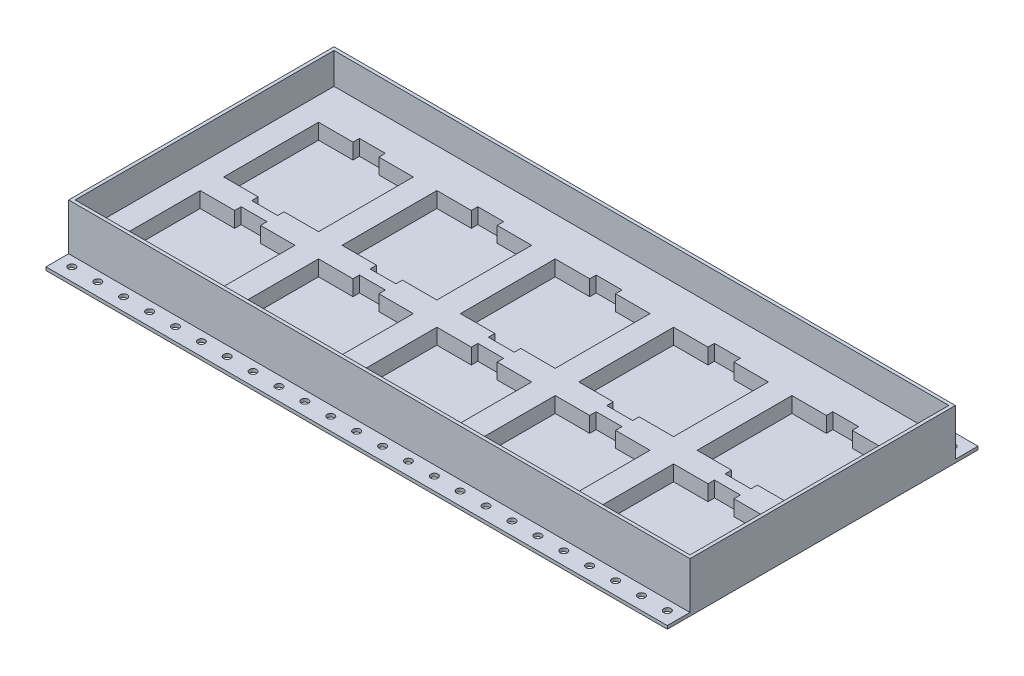
SolidWorks part; units mm, degrees
ref_plane "Front Plane" through (0, 0, 0) normal (0, 0, 1) x (1, 0, 0)
ref_plane "Top Plane" through (0, 0, 0) normal (0, 1, 0) x (1, 0, 0)
ref_plane "Right Plane" through (0, 0, 0) normal (1, 0, 0) x (0, 0, -1)
sketch "Sketch1" plane through (0, 0, 0) normal (0, 1, 0) x (1, 0, 0)
  line L0 (-185.728, 88.9) -> (-162.614, 88.9) construction
  line L1 (-304.8, -152.4) -> (304.8, -152.4)
  line L2 (-304.8, -152.4) -> (-304.8, 152.4)
  line L3 (-304.8, 152.4) -> (304.8, 152.4)
  line L4 (304.8, -152.4) -> (304.8, 152.4)
  line L5 (46.5, -4.1) -> (-46.5, -4.1)
  line L6 (46.5, -4.1) -> (46.5, 88.9)
  line L7 (-69.614, 88.9) -> (-162.614, 88.9)
  line L8 (-69.614, 88.9) -> (-69.614, -4.1)
  line L9 (-69.614, -4.1) -> (-162.614, -4.1)
  line L10 (-162.614, 88.9) -> (-162.614, -4.1)
  line L11 (-69.614, 88.9) -> (-162.614, -4.1) construction
  line L12 (-69.614, -4.1) -> (-162.614, 88.9) construction
  line L13 (46.5, 88.9) -> (-46.5, 88.9)
  line L14 (-46.5, -4.1) -> (-46.5, 88.9)
  line L15 (46.5, -4.1) -> (-46.5, 88.9) construction
  line L16 (46.5, 88.9) -> (-46.5, -4.1) construction
  line L17 (-162.614, -27.214) -> (-69.614, -27.214)
  line L18 (-162.614, -27.214) -> (-162.614, -120.214)
  line L19 (-162.614, -120.214) -> (-69.614, -120.214)
  line L20 (-69.614, -27.214) -> (-69.614, -120.214)
  line L21 (-162.614, -27.214) -> (-69.614, -120.214) construction
  line L22 (-162.614, -120.214) -> (-69.614, -27.214) construction
  line L23 (-46.5, -27.214) -> (46.5, -27.214)
  line L24 (-46.5, -27.214) -> (-46.5, -120.214)
  line L25 (-46.5, -120.214) -> (46.5, -120.214)
  line L26 (46.5, -27.214) -> (46.5, -120.214)
  line L27 (-46.5, -27.214) -> (46.5, -120.214) construction
  line L28 (-46.5, -120.214) -> (46.5, -27.214) construction
  line L29 (-278.728, 88.9) -> (-185.728, 88.9)
  line L30 (-278.728, 88.9) -> (-278.728, -4.1)
  line L31 (-278.728, -4.1) -> (-185.728, -4.1)
  line L32 (-185.728, 88.9) -> (-185.728, -4.1)
  line L33 (-278.728, -27.214) -> (-185.728, -27.214)
  line L34 (-278.728, -27.214) -> (-278.728, -120.214)
  line L35 (-278.728, -120.214) -> (-185.728, -120.214)
  line L36 (-185.728, -27.214) -> (-185.728, -120.214)
  line L37 (69.614, 88.9) -> (162.614, 88.9)
  line L38 (69.614, 88.9) -> (69.614, -4.1)
  line L39 (69.614, -4.1) -> (162.614, -4.1)
  line L40 (162.614, 88.9) -> (162.614, -4.1)
  line L41 (69.614, -27.214) -> (162.614, -27.214)
  line L42 (69.614, -27.214) -> (69.614, -120.214)
  line L43 (69.614, -120.214) -> (162.614, -120.214)
  line L44 (162.614, -27.214) -> (162.614, -120.214)
  line L45 (-69.614, 88.9) -> (-46.5, 88.9) construction
  line L46 (46.5, 88.9) -> (69.614, 88.9) construction
  line L47 (162.614, 88.9) -> (185.728, 88.9) construction
  line L48 (185.728, 88.9) -> (278.728, 88.9)
  line L49 (185.728, 88.9) -> (185.728, -4.1)
  line L50 (185.728, -4.1) -> (278.728, -4.1)
  line L51 (278.728, 88.9) -> (278.728, -4.1)
  line L52 (185.728, -27.214) -> (278.728, -27.214)
  line L53 (185.728, -27.214) -> (185.728, -120.214)
  line L54 (185.728, -120.214) -> (278.728, -120.214)
  line L55 (278.728, -27.214) -> (278.728, -120.214)
  line L56 (69.614, -4.1) -> (69.614, -27.214) construction
  point P0 (0, 0)
  point P6 (-116.114, 42.4)
  point P11 (0, 42.4)
  point P14 (0, 152.4)
  point P16 (-304.8, 0)
  point P18 (-116.114, -73.714)
  point P23 (0, -73.714)
  dimension "D1" = 93
  dimension "D2" = 304.8
  dimension "D3" = 23.114
  dimension "D4" = 23.114
  dimension "D5" = 609.6
  dimension "D6" = 63.5
extrude "Boss-Extrude1" add sketch "Sketch1" along normal blind 15.24
sketch "Sketch2" plane through (0, 0, 0) normal (0, -1, 0) x (-1, 0, 0)
  line L1 (304.8, -152.4) -> (-304.8, -152.4)
  line L2 (304.8, -152.4) -> (304.8, 152.4)
  line L3 (304.8, 152.4) -> (-304.8, 152.4)
  line L4 (-304.8, -152.4) -> (-304.8, 152.4)
extrude "Boss-Extrude2" add sketch "Sketch2" along normal blind 3.175
sketch "Sketch3" plane through (0, 15.24, 0) normal (0, 1, 0) x (1, 0, 0)
  line L1 (-304.8, -152.4) -> (304.8, -152.4)
  line L2 (-304.8, -152.4) -> (-304.8, 152.4)
  line L3 (-304.8, 152.4) -> (304.8, 152.4)
  line L4 (304.8, -152.4) -> (304.8, 152.4)
  line L5 (-301.625, -127) -> (301.625, -127)
  line L6 (-301.625, -127) -> (-301.625, 127)
  line L7 (-301.625, 127) -> (301.625, 127)
  line L8 (301.625, -127) -> (301.625, 127)
  point P10 (-301.625, 0)
  point P11 (0, 127)
  dimension "D1" = 254
  dimension "D2" = 3.175
extrude "Boss-Extrude3" add sketch "Sketch3" along normal blind 30.48
sketch "Sketch4" plane through (0, 45.72, 0) normal (0, 1, 0) x (1, 0, 0)
  line L0 (301.625, 127) -> (-301.625, 127) construction
  line L1 (-304.8, 130.175) -> (304.8, 130.175)
  line L2 (-304.8, 130.175) -> (-304.8, -130.175)
  line L3 (-304.8, -130.175) -> (304.8, -130.175)
  line L4 (304.8, 130.175) -> (304.8, -130.175)
  line L5 (-301.625, 127) -> (-301.625, -127) construction
  line L6 (301.625, -127) -> (301.625, 127) construction
  line L7 (-301.625, -127) -> (301.625, -127) construction
  dimension "D1" = 3.175
  dimension "D2" = 3.175
  dimension "D3" = 3.175
  dimension "D4" = 3.175
extrude "Cut-Extrude1" cut sketch "Sketch4" against normal offset from surface (45.72 mm away) 3.175 flip side to cut up to face at (0, -3.175, 0)
sketch "Sketch5" plane through (0, 0, 0) normal (0, 1, 0) x (1, 0, 0)
  line L0 (304.8, -152.4) -> (-304.8, -152.4) construction
  line L1 (-304.8, -152.4) -> (-304.8, -130.175) construction
  circle A0 centre (-292.1, -139.7) radius 3.4925
  circle A1 centre (-266.7, -139.7) radius 3.4925
  circle A2 centre (-241.3, -139.7) radius 3.4925
  circle A3 centre (-215.9, -139.7) radius 3.4925
  circle A4 centre (-190.5, -139.7) radius 3.4925
  circle A5 centre (-165.1, -139.7) radius 3.4925
  circle A6 centre (-139.7, -139.7) radius 3.4925
  circle A7 centre (-114.3, -139.7) radius 3.4925
  circle A8 centre (-88.9, -139.7) radius 3.4925
  circle A9 centre (-63.5, -139.7) radius 3.4925
  circle A10 centre (-38.1, -139.7) radius 3.4925
  circle A11 centre (-12.7, -139.7) radius 3.4925
  circle A12 centre (12.7, 139.7) radius 3.4925
  circle A13 centre (38.1, 139.7) radius 3.4925
  circle A14 centre (63.5, 139.7) radius 3.4925
  circle A15 centre (88.9, 139.7) radius 3.4925
  circle A16 centre (114.3, 139.7) radius 3.4925
  circle A17 centre (139.7, 139.7) radius 3.4925
  circle A18 centre (165.1, 139.7) radius 3.4925
  circle A19 centre (190.5, 139.7) radius 3.4925
  circle A20 centre (215.9, 139.7) radius 3.4925
  circle A21 centre (241.3, 139.7) radius 3.4925
  circle A22 centre (-292.1, 139.7) radius 3.4925
  circle A23 centre (-266.7, 139.7) radius 3.4925
  circle A24 centre (-241.3, 139.7) radius 3.4925
  circle A25 centre (-215.9, 139.7) radius 3.4925
  circle A26 centre (-190.5, 139.7) radius 3.4925
  circle A27 centre (-165.1, 139.7) radius 3.4925
  circle A28 centre (-139.7, 139.7) radius 3.4925
  circle A29 centre (-114.3, 139.7) radius 3.4925
  circle A30 centre (-88.9, 139.7) radius 3.4925
  circle A31 centre (-63.5, 139.7) radius 3.4925
  circle A32 centre (-38.1, 139.7) radius 3.4925
  circle A33 centre (-12.7, 139.7) radius 3.4925
  circle A34 centre (266.7, 139.7) radius 3.4925
  circle A35 centre (292.1, 139.7) radius 3.4925
  circle A36 centre (12.7, -139.7) radius 3.4925
  circle A37 centre (38.1, -139.7) radius 3.4925
  circle A38 centre (63.5, -139.7) radius 3.4925
  circle A39 centre (88.9, -139.7) radius 3.4925
  circle A40 centre (114.3, -139.7) radius 3.4925
  circle A41 centre (139.7, -139.7) radius 3.4925
  circle A42 centre (165.1, -139.7) radius 3.4925
  circle A43 centre (190.5, -139.7) radius 3.4925
  circle A44 centre (215.9, -139.7) radius 3.4925
  circle A45 centre (241.3, -139.7) radius 3.4925
  circle A46 centre (266.7, -139.7) radius 3.4925
  circle A47 centre (292.1, -139.7) radius 3.4925
  circle A53 centre (-292.1, -114.3) radius 3.4925 [skipped]
  circle A54 centre (-292.1, -88.9) radius 3.4925 [skipped]
  circle A55 centre (-292.1, -63.5) radius 3.4925 [skipped]
  circle A56 centre (-292.1, -38.1) radius 3.4925 [skipped]
  circle A57 centre (-292.1, -12.7) radius 3.4925 [skipped]
  circle A58 centre (-292.1, 12.7) radius 3.4925 [skipped]
  circle A59 centre (-292.1, 38.1) radius 3.4925 [skipped]
  circle A60 centre (-292.1, 63.5) radius 3.4925 [skipped]
  circle A61 centre (-292.1, 88.9) radius 3.4925 [skipped]
  circle A62 centre (-292.1, 114.3) radius 3.4925 [skipped]
  dimension "D1" = 6.985
  dimension "D2" = 12.7
  dimension "D3" = 12.7
  dimension "D4" = 24
  dimension "D5" = 12
  dimension "D6" = 24
extrude "Cut-Extrude2" cut sketch "Sketch5" against normal through all
sketch "Sketch6" plane through (0, 15.24, 0) normal (0, 1, 0) x (1, 0, 0)
  line L0 (-69.614, 88.9) -> (-162.614, 88.9) construction
  line L1 (-128.814, 88.9) -> (-103.414, 88.9)
  line L2 (-128.814, 88.9) -> (-128.814, 95.25)
  line L3 (-128.814, 95.25) -> (-103.414, 95.25)
  line L4 (-103.414, 88.9) -> (-103.414, 95.25)
  line L5 (-46.5, -120.214) -> (46.5, -120.214) construction
  line L6 (-69.614, -27.214) -> (-162.614, -27.214) construction
  line L7 (-128.814, -27.214) -> (-103.414, -27.214)
  line L8 (-128.814, -27.214) -> (-128.814, -20.864)
  line L9 (-128.814, -20.864) -> (-103.414, -20.864)
  line L10 (-162.614, -4.1) -> (-69.614, -4.1) construction
  line L11 (-128.814, -4.1) -> (-103.414, -4.1)
  line L12 (-128.814, -4.1) -> (-128.814, -10.45)
  line L13 (-128.814, -10.45) -> (-103.414, -10.45)
  line L14 (-103.414, -4.1) -> (-103.414, -10.45)
  line L15 (-103.414, -27.214) -> (-103.414, -20.864)
  line L16 (-162.614, -120.214) -> (-69.614, -120.214) construction
  line L17 (-128.814, -120.214) -> (-103.414, -120.214)
  line L18 (-128.814, -120.214) -> (-128.814, -126.564)
  line L19 (-128.814, -126.564) -> (-103.414, -126.564)
  line L20 (-103.414, -120.214) -> (-103.414, -126.564)
  line L21 (12.7, -120.214) -> (-12.7, -120.214)
  line L22 (12.7, -120.214) -> (12.7, -126.564)
  line L23 (12.7, -126.564) -> (-12.7, -126.564)
  line L24 (-12.7, -120.214) -> (-12.7, -126.564)
  line L25 (46.5, -27.214) -> (-46.5, -27.214) construction
  line L26 (12.7, -27.214) -> (-12.7, -27.214)
  line L27 (12.7, -27.214) -> (12.7, -20.864)
  line L28 (12.7, -20.864) -> (-12.7, -20.864)
  line L29 (-12.7, -27.214) -> (-12.7, -20.864)
  line L30 (-46.5, -4.1) -> (46.5, -4.1) construction
  line L31 (12.7, -4.1) -> (-12.7, -4.1)
  line L32 (12.7, -4.1) -> (12.7, -10.45)
  line L33 (12.7, -10.45) -> (-12.7, -10.45)
  line L34 (-12.7, -4.1) -> (-12.7, -10.45)
  line L35 (46.5, 88.9) -> (-46.5, 88.9) construction
  line L36 (12.7, 88.9) -> (-12.7, 88.9)
  line L37 (12.7, 88.9) -> (12.7, 95.25)
  line L38 (12.7, 95.25) -> (-12.7, 95.25)
  line L39 (-12.7, 88.9) -> (-12.7, 95.25)
  line L40 (-185.728, 88.9) -> (-278.728, 88.9) construction
  line L41 (-219.528, 95.25) -> (-244.928, 95.25)
  line L42 (-219.528, 95.25) -> (-219.528, 88.9)
  line L43 (-219.528, 88.9) -> (-244.928, 88.9)
  line L44 (-244.928, 95.25) -> (-244.928, 88.9)
  line L45 (-278.728, -4.1) -> (-185.728, -4.1) construction
  line L46 (-219.528, -10.45) -> (-244.928, -10.45)
  line L47 (-219.528, -10.45) -> (-219.528, -4.1)
  line L48 (-219.528, -4.1) -> (-244.928, -4.1)
  line L49 (-244.928, -10.45) -> (-244.928, -4.1)
  line L50 (-185.728, -27.214) -> (-278.728, -27.214) construction
  line L51 (-219.528, -20.864) -> (-244.928, -20.864)
  line L52 (-219.528, -20.864) -> (-219.528, -27.214)
  line L53 (-219.528, -27.214) -> (-244.928, -27.214)
  line L54 (-244.928, -20.864) -> (-244.928, -27.214)
  line L55 (-278.728, -120.214) -> (-185.728, -120.214) construction
  line L56 (-219.528, -126.564) -> (-244.928, -126.564)
  line L57 (-219.528, -126.564) -> (-219.528, -120.214)
  line L58 (-219.528, -120.214) -> (-244.928, -120.214)
  line L59 (-244.928, -126.564) -> (-244.928, -120.214)
  line L60 (69.614, -120.214) -> (162.614, -120.214) construction
  line L61 (128.814, -126.564) -> (103.414, -126.564)
  line L62 (128.814, -126.564) -> (128.814, -120.214)
  line L63 (128.814, -120.214) -> (103.414, -120.214)
  line L64 (103.414, -126.564) -> (103.414, -120.214)
  line L65 (162.614, -27.214) -> (69.614, -27.214) construction
  line L66 (128.814, -20.864) -> (103.414, -20.864)
  line L67 (128.814, -20.864) -> (128.814, -27.214)
  line L68 (128.814, -27.214) -> (103.414, -27.214)
  line L69 (103.414, -20.864) -> (103.414, -27.214)
  line L70 (69.614, -4.1) -> (162.614, -4.1) construction
  line L71 (128.814, -10.45) -> (103.414, -10.45)
  line L72 (128.814, -10.45) -> (128.814, -4.1)
  line L73 (128.814, -4.1) -> (103.414, -4.1)
  line L74 (103.414, -10.45) -> (103.414, -4.1)
  line L75 (162.614, 88.9) -> (69.614, 88.9) construction
  line L76 (128.814, 95.25) -> (103.414, 95.25)
  line L77 (128.814, 95.25) -> (128.814, 88.9)
  line L78 (128.814, 88.9) -> (103.414, 88.9)
  line L79 (103.414, 95.25) -> (103.414, 88.9)
  line L80 (278.728, 88.9) -> (185.728, 88.9) construction
  line L81 (244.928, 95.25) -> (219.528, 95.25)
  line L82 (244.928, 95.25) -> (244.928, 88.9)
  line L83 (244.928, 88.9) -> (219.528, 88.9)
  line L84 (219.528, 95.25) -> (219.528, 88.9)
  line L85 (185.728, -4.1) -> (278.728, -4.1) construction
  line L86 (244.928, -10.45) -> (219.528, -10.45)
  line L87 (244.928, -10.45) -> (244.928, -4.1)
  line L88 (244.928, -4.1) -> (219.528, -4.1)
  line L89 (219.528, -10.45) -> (219.528, -4.1)
  line L90 (278.728, -27.214) -> (185.728, -27.214) construction
  line L91 (244.928, -20.864) -> (219.528, -20.864)
  line L92 (244.928, -20.864) -> (244.928, -27.214)
  line L93 (244.928, -27.214) -> (219.528, -27.214)
  line L94 (219.528, -20.864) -> (219.528, -27.214)
  line L95 (185.728, -120.214) -> (278.728, -120.214) construction
  line L96 (244.928, -126.564) -> (219.528, -126.564)
  line L97 (244.928, -126.564) -> (244.928, -120.214)
  line L98 (244.928, -120.214) -> (219.528, -120.214)
  line L99 (219.528, -126.564) -> (219.528, -120.214)
  point P27 (-116.114, -4.1)
  point P28 (-116.114, -10.45)
  point P29 (-116.114, 88.9)
  point P30 (-116.114, 95.25)
  point P55 (0, -120.214)
  point P132 (-232.228, 88.9)
  point P133 (-232.228, 88.9)
  point P136 (116.114, 88.9)
  point P137 (116.114, 95.25)
  point P139 (232.228, 88.9)
  point P140 (232.228, 95.25)
  dimension "D1" = 25.4
  dimension "D2" = 6.35
  dimension "D3" = 6.35
extrude "Cut-Extrude3" cut sketch "Sketch6" against normal up to surface (15.24 mm away) up to face at (-116.114, 0, -42.4)
